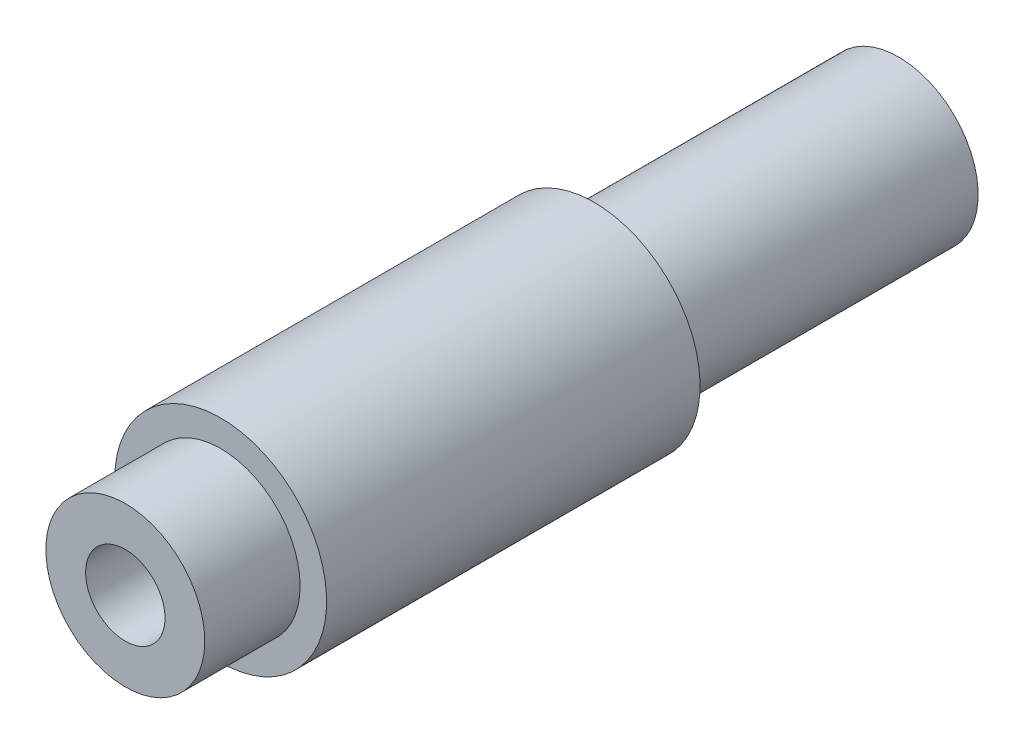
SolidWorks part; units mm, degrees
material "1060 合金"
ref_plane "正面" through (0, 0, 0) normal (0, 0, 1) x (1, 0, 0)
ref_plane "平面" through (0, 0, 0) normal (0, 1, 0) x (1, 0, 0)
ref_plane "右側面" through (0, 0, 0) normal (1, 0, 0) x (0, 0, -1)
sketch "ｽｹｯﾁ1" plane through (0, 0, 0) normal (0, 0, 1) x (1, 0, 0)
  circle A0 centre (0, 0) radius 4
  circle A1 centre (0, 0) radius 1.5
  dimension "D1" = 8
  dimension "D2" = 3
extrude "ﾎﾞｽ - 押し出し3" add sketch "ｽｹｯﾁ1" along normal blind 29.2
sketch "ｽｹｯﾁ3" plane through (0, 0, 0) normal (0, 0, -1) x (-1, 0, 0)
  circle A0 centre (0, 0) radius 1.5
  circle A1 centre (0, 0) radius 3
  circle A3 centre (0, 0) radius 4
  circle M1 centre (0, 0) radius 4
  dimension "D1" = 6
  dimension "D2" = 3
  dimension "D3" = 8
extrude "ｶｯﾄ - 押し出し1" cut sketch "ｽｹｯﾁ3" against normal blind 11.5 contours A1 M1
sketch "ｽｹｯﾁ4" plane through (0, 0, 29.2) normal (0, 0, 1) x (1, 0, 0)
  circle A0 centre (0, 0) radius 3
  circle A1 centre (0, 0) radius 4
  dimension "D1" = 8
  dimension "D2" = 6
extrude "ｶｯﾄ - 押し出し2" cut sketch "ｽｹｯﾁ4" against normal blind 3.6
